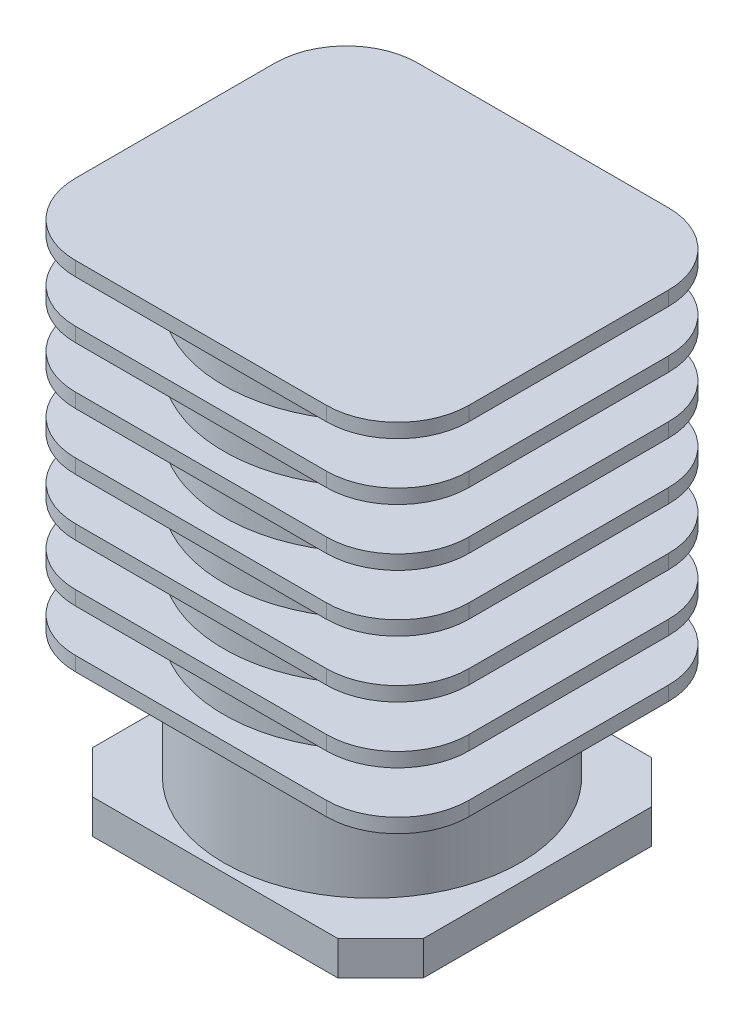
SolidWorks part; units mm, degrees
ref_plane "Front Plane" through (0, 0, 0) normal (0, 0, 1) x (1, 0, 0)
ref_plane "Top Plane" through (0, 0, 0) normal (0, 1, 0) x (1, 0, 0)
ref_plane "Right Plane" through (0, 0, 0) normal (1, 0, 0) x (0, 0, -1)
sketch "Sketch1" plane through (0, 0, 0) normal (0, 1, 0) x (1, 0, 0)
  circle A0 centre (0, 0) radius 52
extrude "Boss-Extrude1" add sketch "Sketch1" against normal blind 165
sketch "Sketch2" plane through (0, 0, 0) normal (0, 1, 0) x (1, 0, 0)
  line L1 (-44, -60) -> (44, -60)
  line L2 (-69, -35) -> (-69, 35)
  line L3 (-44, 60) -> (44, 60)
  line L4 (69, -35) -> (69, 35)
  line L5 (-69, -60) -> (69, 60) construction
  line L6 (-69, 60) -> (69, -60) construction
  arc A0 (-44, -60) -> (-69, -35) centre (-44, -35) cw
  arc A1 (44, -60) -> (69, -35) centre (44, -35) ccw
  arc A2 (44, 60) -> (69, 35) centre (44, 35) cw
  arc A3 (-69, 35) -> (-44, 60) centre (-44, 35) cw
  point P0 (0, 0)
  dimension "D3" = 25
  dimension "D1" = 138
  dimension "D2" = 120
extrude "Boss-Extrude2" add sketch "Sketch2" against normal blind 5
pattern_linear "LPattern1" count 7 spacing 20 along (0, -1, 0) of "Boss-Extrude2"
sketch "Sketch3" plane through (0, -165, 0) normal (0, -1, 0) x (1, 0, 0)
  line L0 (-43, 55) -> (-58, 40)
  line L1 (-43, -55) -> (43, -55)
  line L7 (-58, -40) -> (-58, 40)
  line L8 (-43, 55) -> (43, 55)
  line L13 (58, -40) -> (58, 40)
  line L16 (-43, -55) -> (-58, -40)
  line L17 (43, -55) -> (58, -40)
  line L18 (43, 55) -> (58, 40)
  point P0 (0, 0)
extrude "Boss-Extrude3" add sketch "Sketch3" along normal blind 12
sketch "Sketch4" plane through (0, -177, 0) normal (0, -1, 0) x (1, 0, 0)
  circle A0 centre (0, 0) radius 47
  dimension "D1" = 94
extrude "Cut-Extrude1" cut sketch "Sketch4" against normal blind 172
